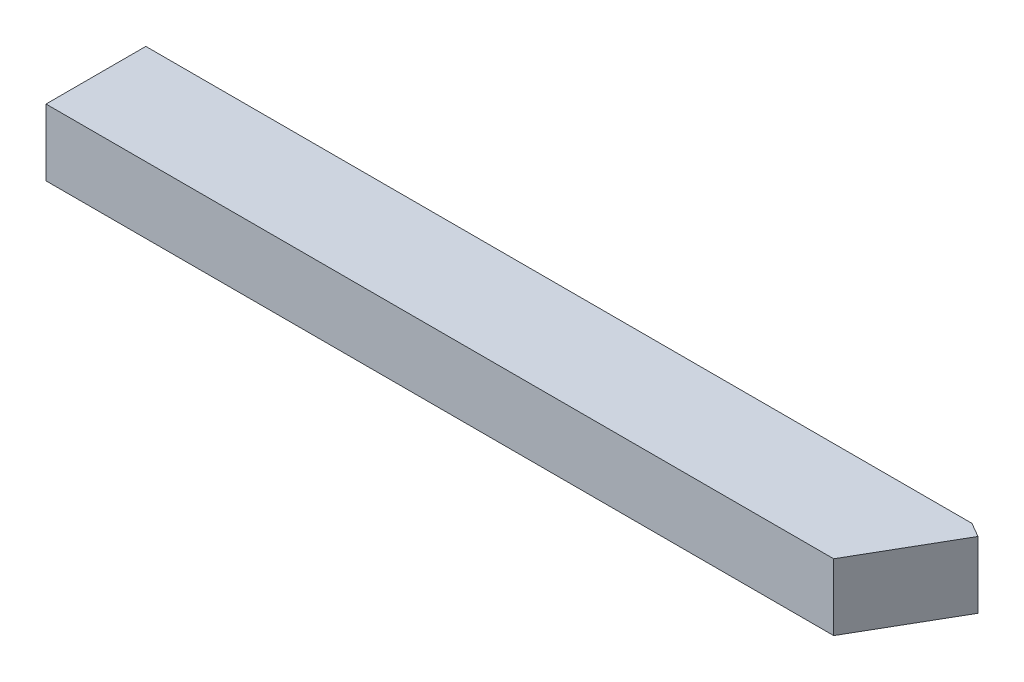
SolidWorks part; units mm, degrees
material "Pine"
ref_plane "X-Y Datum" through (0, 0, 0) normal (0, 0, 1) x (1, 0, 0)
ref_plane "X-Z Datum" through (0, 0, 0) normal (0, 1, 0) x (1, 0, 0)
ref_plane "Y-Z Datum" through (0, 0, 0) normal (1, 0, 0) x (0, 0, -1)
sketch "Sketch1" plane through (0, 0, 0) normal (1, 0, 0) x (0, 0, -1)
  line L1 (-12.7, 12.7) -> (12.7, 12.7)
  line L2 (-12.7, 12.7) -> (-12.7, -12.7)
  line L3 (-12.7, -12.7) -> (12.7, -12.7)
  line L4 (12.7, 12.7) -> (12.7, -12.7)
  line L5 (-12.7, 12.7) -> (12.7, -12.7) construction
  line L6 (-12.7, -12.7) -> (12.7, 12.7) construction
  point P0 (0, 0)
  dimension "D1" = 25.4
extrude "Boss-Extrude1" add sketch "Sketch1" along normal blind 307.975
sketch "Sketch2" plane through (0, 12.7, 0) normal (0, 1, 0) x (1, 0, 0)
  line L0 (307.975, -12.7) -> (320.8066, 9.525)
  line L1 (320.8066, 12.7) -> (307.975, 12.7)
  line L2 (307.975, 12.7) -> (307.975, -12.7)
  line L3 (320.8066, 9.525) -> (320.8066, 12.7)
  dimension "D1" = 30
  dimension "D2" = 3.175
extrude "Boss-Extrude2" add sketch "Sketch2" against normal up to surface (25.4 mm away) up to face at (153.9875, -12.7, 0)
sketch "Sketch3" plane through (0, 12.7, 0) normal (0, 1, 0) x (1, 0, 0)
  line L0 (320.8066, 9.525) -> (315.3073, 12.7)
  line L1 (320.8066, 12.7) -> (0, 12.7) construction
  line L2 (307.975, -12.7) -> (320.8066, 9.525) construction
  line L3 (315.3073, 12.7) -> (320.8066, 12.7)
  line L4 (320.8066, 12.7) -> (320.8066, 9.525)
extrude "Cut-Extrude1" cut sketch "Sketch3" against normal through all both and the other way through all
sketch "Sketch4" plane through (0, 12.7, 0) normal (0, 1, 0) x (1, 0, 0)
  line L5 (307.975, -12.7) -> (0, -12.7) construction
  line L6 (0, -12.7) -> (0, -25.4)
  line L7 (0, -25.4) -> (300.6427, -25.4)
  line L8 (300.6427, -25.4) -> (307.975, -12.7)
  line L9 (307.975, -12.7) -> (0, -12.7)
  line L10 (307.975, -12.7) -> (320.8066, 9.525) construction
  line L11 (315.3073, 12.7) -> (0, 12.7) construction
  dimension "D1" = 38.1
extrude "Boss-Extrude3" add sketch "Sketch4" against normal up to surface (25.4 mm away) up to face at (188.8178, -12.7, -1.905)
